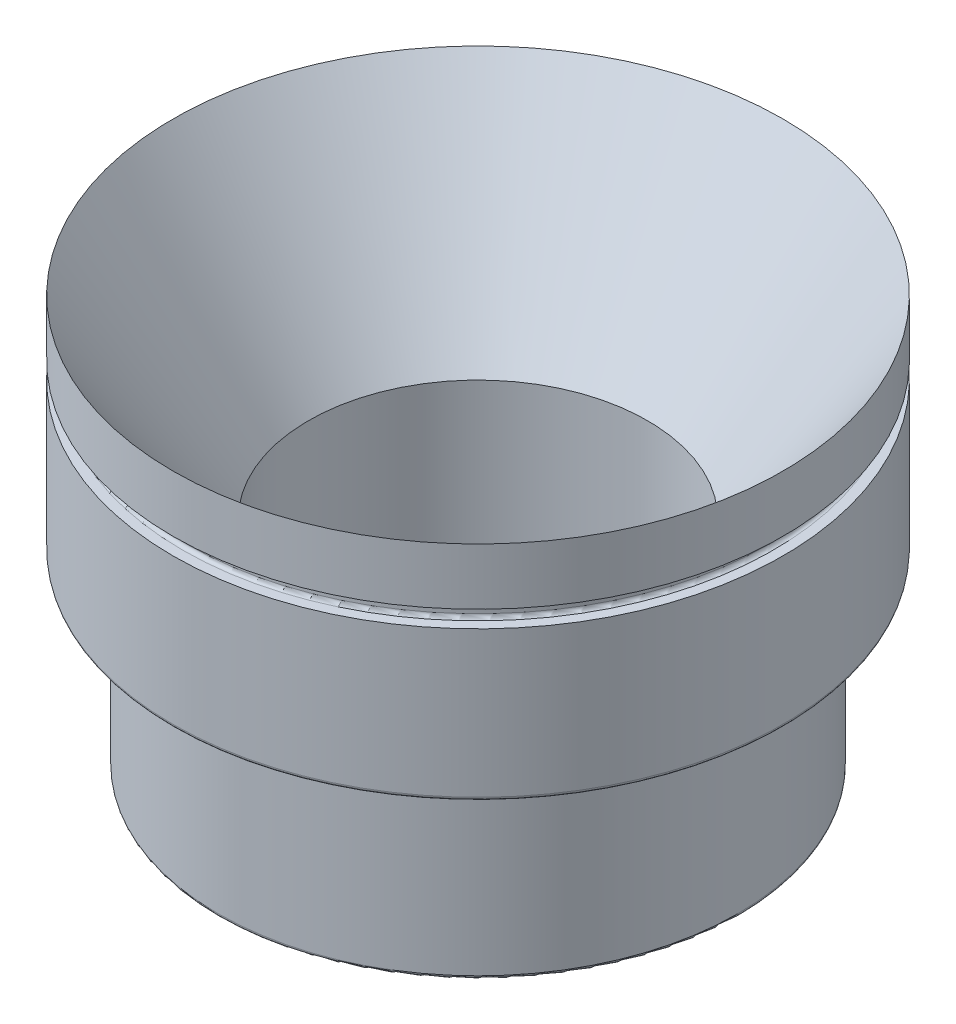
SolidWorks part; units mm, degrees
material "C (Graphite)"
ref_plane "Front Plane" through (0, 0, 0) normal (0, 0, 1) x (1, 0, 0)
ref_plane "Top Plane" through (0, 0, 0) normal (0, 1, 0) x (1, 0, 0)
ref_plane "Right Plane" through (0, 0, 0) normal (1, 0, 0) x (0, 0, -1)
sketch "Sketch4" plane through (0, 0, 0) normal (1, 0, 0) x (0, 0, -1)
  line L0 (0, 0) -> (0, -131.2074) construction
  line L1 (34.2773, 0) -> (23.8732, -14.8586) construction
  line L2 (19.05, -81.8573) -> (19.05, -89.5311) construction
  line L3 (22.2956, -54.8084) -> (51.1382, -162.4506) construction
  line L4 (34.2773, 0) -> (19.05, -21.7468)
  line L17 (34.2773, 0) -> (34.2773, -25.0505)
  line L18 (34.2773, -25.0505) -> (29.1846, -25.0505)
  line L19 (29.1846, -25.0505) -> (29.1846, -46.0309)
  line L20 (29.1846, -46.0309) -> (20.3822, -46.0309)
  line L22 (20.3822, -46.0309) -> (19.05, -38.1493)
  line L24 (19.05, -21.7468) -> (19.05, -38.1493)
  arc A1 (23.8732, -14.8586) -> (19.05, -30.1559) centre (45.72, -30.1559) ccw construction
  arc A2 (19.05, -30.1559) -> (22.2956, -54.8084) centre (114.3, -30.1559) ccw construction
  dimension "D4" = 26.67
  dimension "D6" = 95.25
  dimension "D3" = 35
  dimension "D5" = 38.1
  dimension "D7" = 15
  dimension "D15" = 3.2456
  dimension "D19" = 10.1346
  dimension "D20" = 5.1054
  dimension "D21" = 15.875
  dimension "D11" = 68.5546
  dimension "D24" = 58.3692
revolve "Revolve1" add sketch "Sketch4" angle 360 about L0
sketch "Sketch6" plane through (0, 0, 0) normal (1, 0, 0) x (0, 0, -1)
  line L0 (34.2773, -6.35) -> (32.766, -6.35)
  line L1 (32.766, -6.35) -> (32.766, -8.255)
  line L2 (32.766, -8.255) -> (34.2773, -8.255)
  line L3 (34.2773, -8.255) -> (34.2773, -6.35)
  line L4 (-34.2773, 0) -> (34.2773, 0) construction
  line L5 (-34.2773, 0) -> (34.2773, 0) construction
  line L6 (0, 11.3644) -> (0, 4.9299) construction
  dimension "D1" = 65.532
  dimension "D2" = 1.905
  dimension "D3" = 6.35
revolve "Spring Groove" cut sketch "Sketch6" angle 360 about L6
fillet "Tool Radius" radius 0.4064 5 edges at (0, -46.0309, 29.1846) (0, -25.0505, 34.2773) (0, -6.35, 32.766) (0, -8.255, 32.766) (0, -25.0505, 29.1846)
equation "\"Dc\"= 114.30mm"
equation "\"Dt\"= 38.1mm"
equation "\"R1\"= 26.67mm"
equation "\"R2\"= 92mm"
equation "\"b\"= 35deg"
equation "\"Rn\"= 95.25mm"
equation "\"Tn\"= 15deg"
equation "\"Te\"= 3deg"
equation "\"De\"= 87.31mm"
equation "\"Le\"= 146.71mm"
equation "\"D5@Sketch4\"=\"Dt\""
equation "\"WallThickness\"=0.5"
equation "\"D20@Sketch4\"=0.200in+.001in"
equation "\"Rt\"=1.5"
